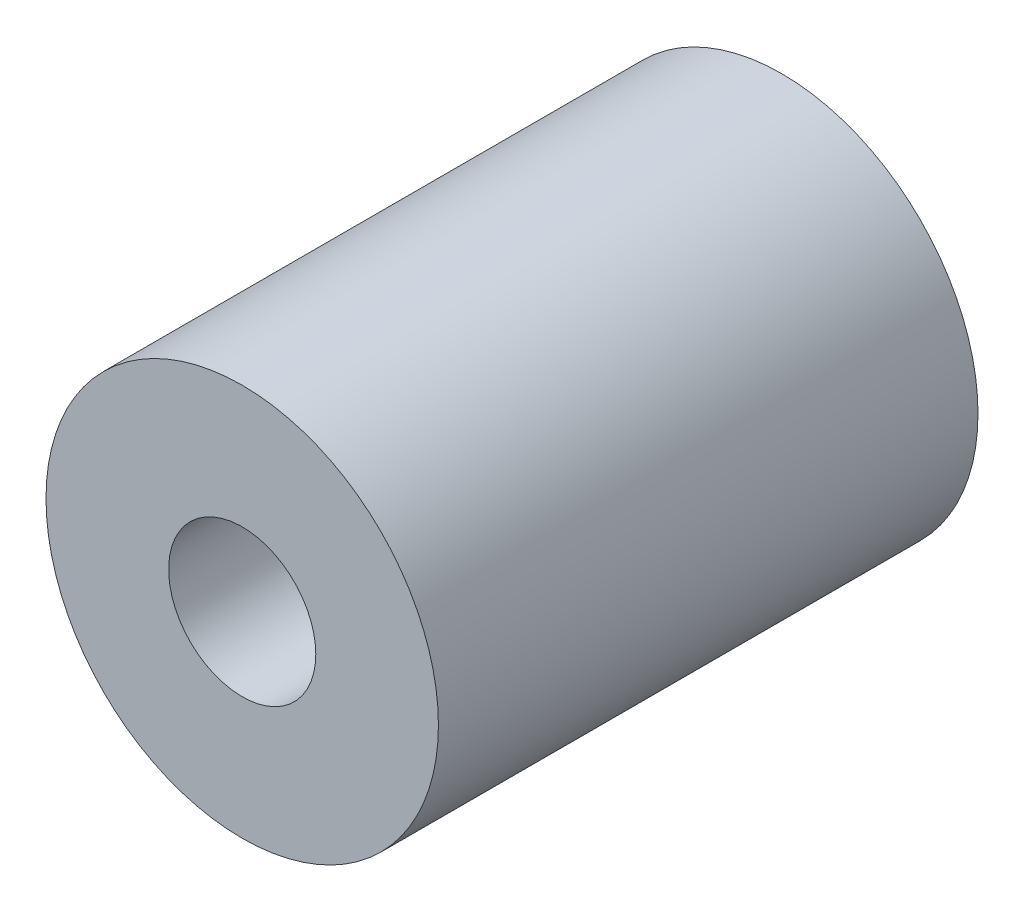
SolidWorks part; units mm, degrees
material "Plain Carbon Steel"
ref_plane "Front Plane" through (0, 0, 0) normal (0, 0, 1) x (1, 0, 0)
ref_plane "Top Plane" through (0, 0, 0) normal (0, 1, 0) x (1, 0, 0)
ref_plane "Right Plane" through (0, 0, 0) normal (1, 0, 0) x (0, 0, -1)
sketch "Sketch1" plane through (0, 0, 0) normal (0, 0, 1) x (1, 0, 0)
  circle A0 centre (0, 0) radius 3
  circle A1 centre (0, 0) radius 8
  dimension "D1" = 6
  dimension "D2" = 16
extrude "Boss-Extrude1" add sketch "Sketch1" along normal mid plane 22
